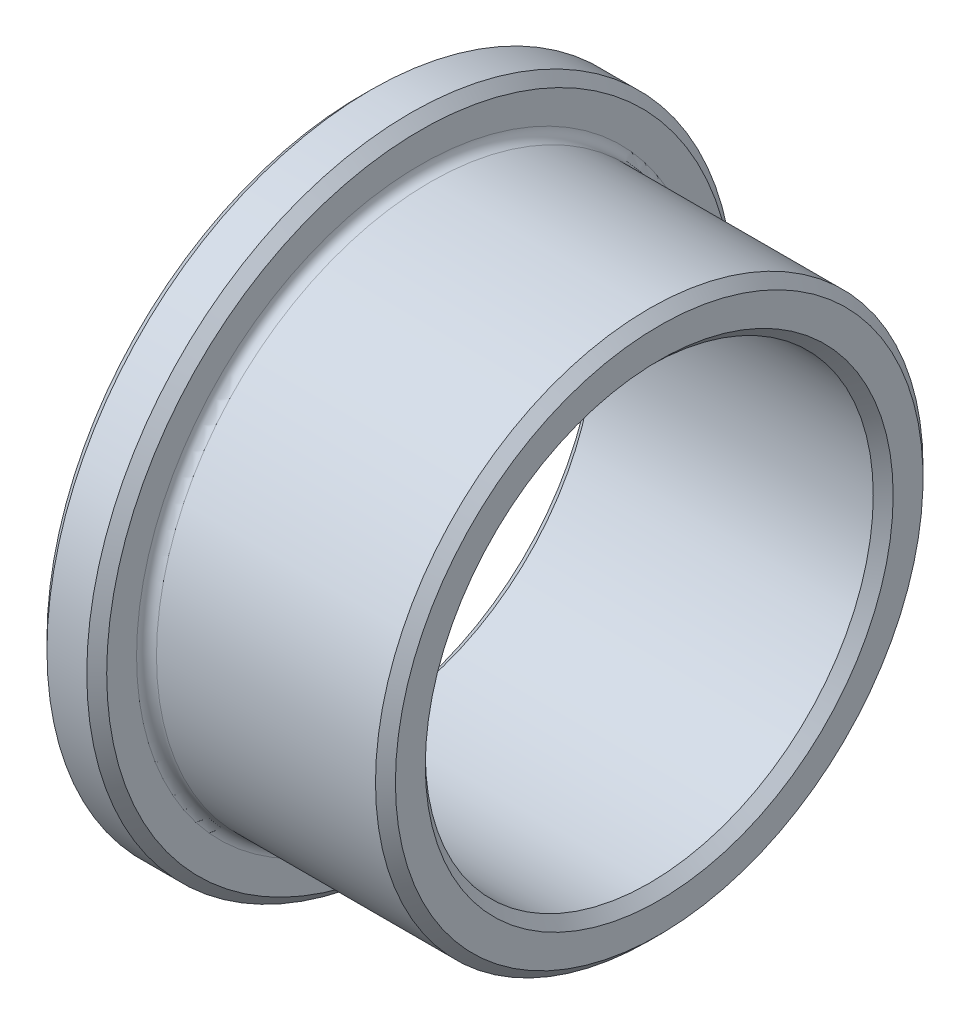
SolidWorks part; units mm, degrees
material "Phosphor bronze 10% D, UNS C52400"
ref_plane "Front Plane" through (0, 0, 0) normal (0, 0, 1) x (1, 0, 0)
ref_plane "Top Plane" through (0, 0, 0) normal (0, 1, 0) x (1, 0, 0)
ref_plane "Right Plane" through (0, 0, 0) normal (1, 0, 0) x (0, 0, -1)
sketch "Sketch1" plane through (0, 0, 0) normal (0, 0, 1) x (1, 0, 0)
  line L0 (0, 22.5) -> (30, 22.5)
  line L1 (30, 22.5) -> (30, 27.5)
  line L2 (30, 27.5) -> (6, 27.5)
  line L3 (6, 27.5) -> (6, 32.5)
  line L4 (6, 32.5) -> (0, 32.5)
  line L5 (0, 32.5) -> (0, 22.5)
  line L6 (0, 0) -> (44.8454, 0) construction
  dimension "D1" = 45
  dimension "D2" = 6
  dimension "D3" = 65
  dimension "D4" = 30
  dimension "D5" = 55
revolve "Revolve1" add sketch "Sketch1" angle 360 about L6
chamfer "Chamfer1" distance 1 angle 45 5 edges at (0, 0, 22.5) (30, 0, 22.5) (6, 0, 32.5) (0, 0, 32.5) (30, 0, 27.5)
fillet "Fillet1" radius 1 1 edges at (6, 0, 27.5)
